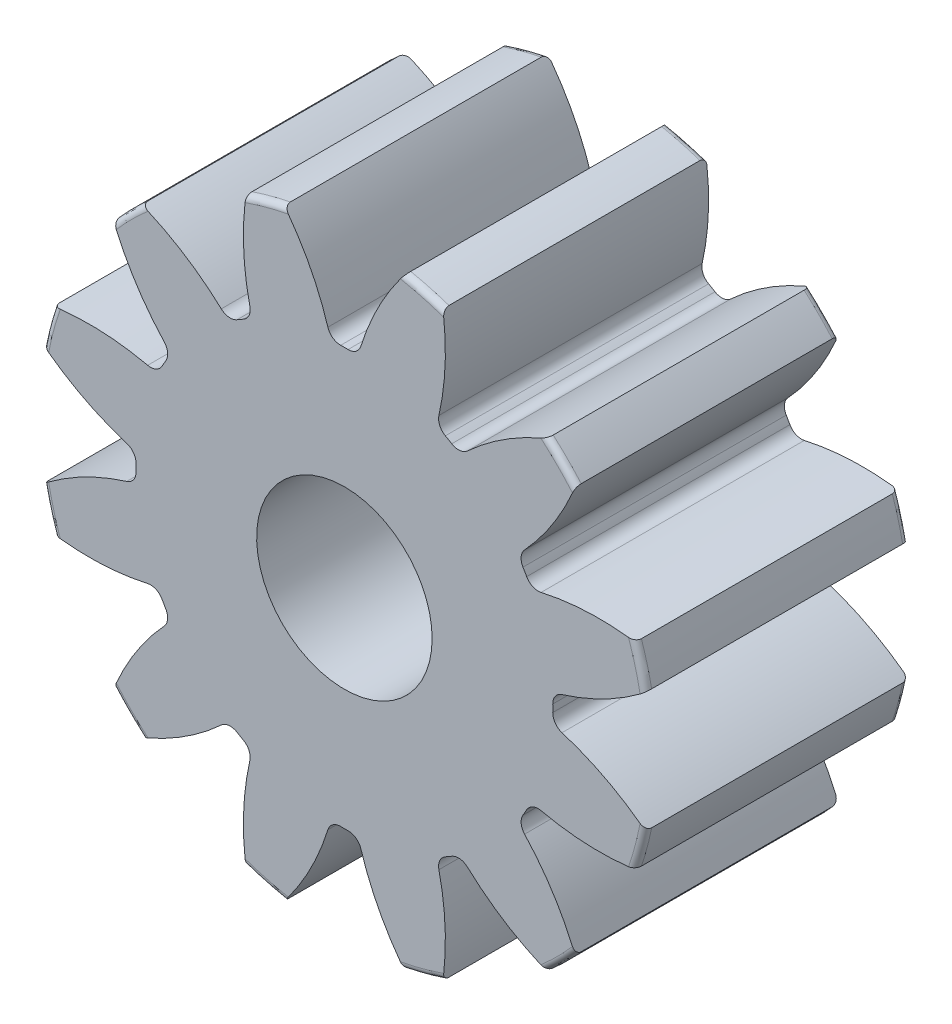
SolidWorks part; units mm, degrees
ref_plane "Front Plane" through (0, 0, 0) normal (0, 0, 1) x (1, 0, 0)
ref_plane "Top Plane" through (0, 0, 0) normal (0, 1, 0) x (1, 0, 0)
ref_plane "Right Plane" through (0, 0, 0) normal (1, 0, 0) x (0, 0, -1)
sketch "Sketch1" plane through (0, 0, 0) normal (0, 0, 1) x (1, 0, 0)
  line L0 (-152.4, 0) -> (152.4, 0) construction
  circle A0 centre (0, 0) radius 3.5 construction
  circle A1 centre (0, 0) radius 3 construction
  circle A2 centre (0, 0) radius 2.375 construction
  circle A3 centre (0, 0) radius 2.25 construction
  circle A4 centre (0, 0) radius 1 construction
  dimension "D2" = 0.5
  dimension "D3" = 1.125
  dimension "D1" = 1.125
sketch "Sketch2" plane through (0, 0, 0) normal (1, 0, 0) x (0, 0, -1)
  line L0 (0, 0) -> (-3, 0) construction
  line L1 (-3, 0) -> (-7, 0) construction
  dimension "Overall Width" = 7
  dimension "Face Width" = 3
sketch "Sketch4" plane through (0, 0, 0) normal (1, 0, 0) x (0, 0, -1)
  line L0 (-7, 1) -> (-7, 2.25)
  line L1 (-7, 2.25) -> (-3, 2.25)
  line L2 (-3, 2.25) -> (-3, 3.5)
  line L3 (-3, 3.5) -> (0, 3.5)
  line L4 (0, 3.5) -> (0, 1)
  line L5 (-3, 2.25) -> (-3, 0) construction
  line L6 (0, 3.5) -> (0, -3.5) construction
  line L7 (-3, 2.25) -> (0, 2.25) construction
  line L12 (-7, 1) -> (0, 1)
revolve "Revolve1" add sketch "Sketch4" angle 360 about L1
fillet "Fillet2" radius 0.07 4 edges at (0, 2.25, 7) (0, 2.25, 3) (0, 3.5, 3) (0, 3.5, 0)
sketch "Sketch7" plane through (0, 0, 3) normal (0, 0, 1) x (1, 0, 0)
  line L0 (0, 0) -> (0, 3.5) construction
  line L1 (0.3916, 2.9743) -> (0.635, 3.4419) construction
  line L3 (0.9059, 3.3807) -> (0.7765, 2.8978) construction
  line L4 (0.7765, 2.8978) -> (0.6147, 2.2941) construction
  line L5 (0, 0) -> (0.6147, 2.2941) construction
  line L6 (0.3916, 2.9743) -> (0, 0) construction
  line L7 (0.3916, 2.9743) -> (0.4568, 3.4701) construction
  line L8 (0.3916, 2.9743) -> (0, 0) construction
  circle A0 centre (0, 0) radius 3.5 construction
  arc A1 (-0.0421, 2.3746) -> (0.0421, 2.3746) centre (0, 0) cw
  circle A2 centre (0, 0) radius 2.375 construction
  arc A3 (-0.3916, 2.9743) -> (0.3916, 2.9743) centre (0, 0) cw construction
  circle A4 centre (0, 0) radius 3 construction
  arc A5 (1.1224, 3.3152) -> (0.6856, 3.4322) centre (0, 0) ccw construction
  arc A6 (0.3916, 2.9743) -> (1.148, 2.7716) centre (0, 0) cw construction
  arc A7 (-0.6856, 3.4322) -> (0.6856, 3.4322) centre (0, 0) cw
  arc A8 (0.188, 2.4801) -> (0.6856, 3.4322) centre (3.0526, 1.5891) cw
  arc A9 (-0.188, 2.4801) -> (-0.6856, 3.4322) centre (-3.0526, 1.5891) ccw
  arc A10 (-0.0421, 2.3746) -> (-0.188, 2.4801) centre (-0.0447, 2.5246) cw
  arc A11 (0.0421, 2.3746) -> (0.188, 2.4801) centre (0.0447, 2.5246) ccw
  point P26 (-0.156, 2.3699)
  point P29 (0.156, 2.3699)
  dimension "D4" = 0.15
  dimension "D5" = 3
  dimension "D3" = 20
  dimension "D1" = 1.5708
  dimension "D2" = 0.7854
extrude "Cut-Extrude2" cut sketch "Sketch7" against normal through all
pattern_circular "CirPattern1" count 12 over 360 about axis through (0, 0, 0) along (0, 0, 1) of "Cut-Extrude2"
sketch "Sketch9" plane through (0, 0, 3) normal (0, 0, 1) x (1, 0, 0)
  circle A0 centre (0, 0) radius 3.5
extrude "Cut-Extrude3" cut sketch "Sketch9" along normal through all
equation "\"D1@Sketch1\"=2.25*(\"Pitch Dia.@Sketch1\"/\"Number of Teeth@Sketch1\")"
equation "\"D1@CirPattern1\"=\"Number of Teeth@Sketch1\""
equation "\"D1@Fillet2\"=\"OD@Sketch1\"*.01"
equation "\"D1@Sketch7\"=3.14159*(\"Pitch Dia.@Sketch1\"/\"Number of Teeth@Sketch1\")"
equation "\"D2@Sketch7\"=\"D1@Sketch7\"/2"
equation "\"D4@Sketch7\"=\"D1@Sketch7\"*.0955"
equation "\"D5@Sketch7\"=\"Pitch Dia.@Sketch1\"/2"
